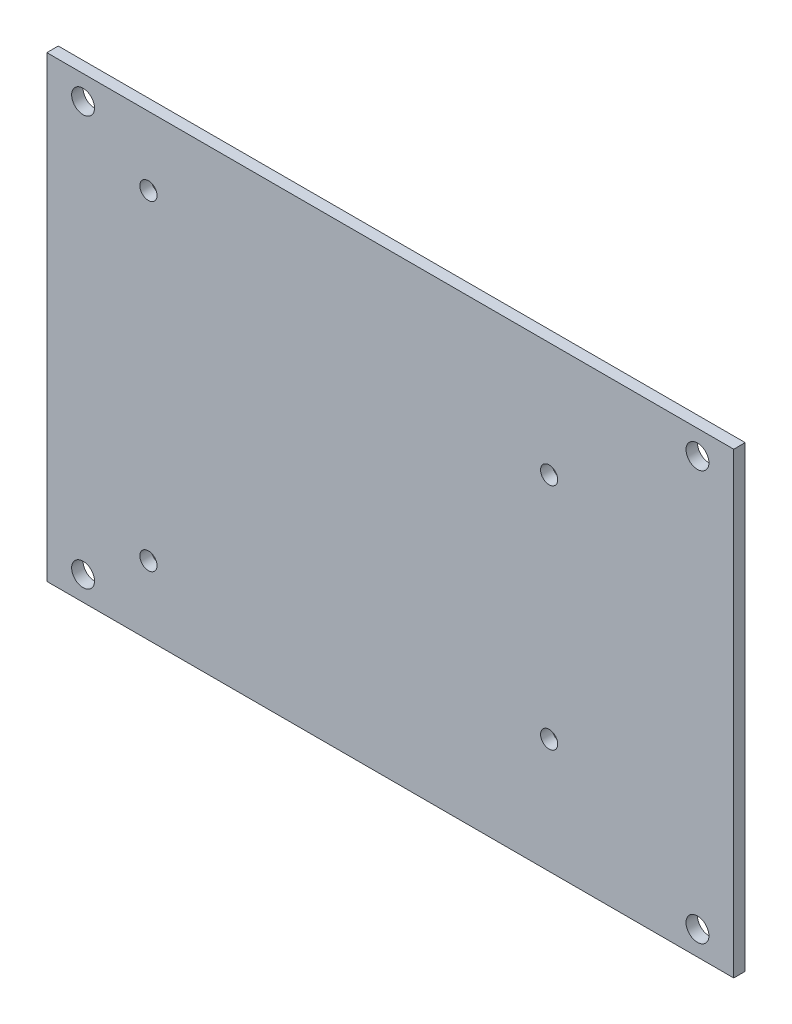
SolidWorks part; units mm, degrees
ref_plane "Front Plane" through (0, 0, 0) normal (0, 0, 1) x (1, 0, 0)
ref_plane "Top Plane" through (0, 0, 0) normal (0, 1, 0) x (1, 0, 0)
ref_plane "Right Plane" through (0, 0, 0) normal (1, 0, 0) x (0, 0, -1)
sketch "Sketch1" plane through (0, 0, 0) normal (0, 0, 1) x (1, 0, 0)
  line L0 (-115.2221, 0) -> (111.5681, 0) construction
  line L5 (0, 56.5544) -> (0, -63.1735) construction
  line L8 (-60, 40) -> (60, 40)
  line L9 (-60, 40) -> (-60, -40)
  line L10 (-60, -40) -> (60, -40)
  line L11 (60, 40) -> (60, -40)
  line L12 (-60, 40) -> (60, -40) construction
  line L13 (-60, -40) -> (60, 40) construction
  circle A0 centre (-42.25, 28) radius 1.5
  circle A1 centre (27.75, 20) radius 1.5
  circle A2 centre (27.75, -20) radius 1.5
  circle A3 centre (-42.25, -28) radius 1.5
  circle A4 centre (-53.6641, 35.7761) radius 2
  circle A5 centre (53.6641, 35.7761) radius 2
  circle A6 centre (53.6641, -35.7761) radius 2
  circle A7 centre (-53.6641, -35.7761) radius 2
  point P0 (0, 0)
  point P8 (0, 0)
  dimension "D5" = 3
  dimension "D8" = 3
  dimension "D1" = 4
  dimension "D2" = 71.5521
  dimension "D3" = 120
  dimension "D4" = 28
  dimension "D6" = 80
  dimension "D7" = 107.3282
extrude "Boss-Extrude3" add sketch "Sketch1" along normal blind 2
